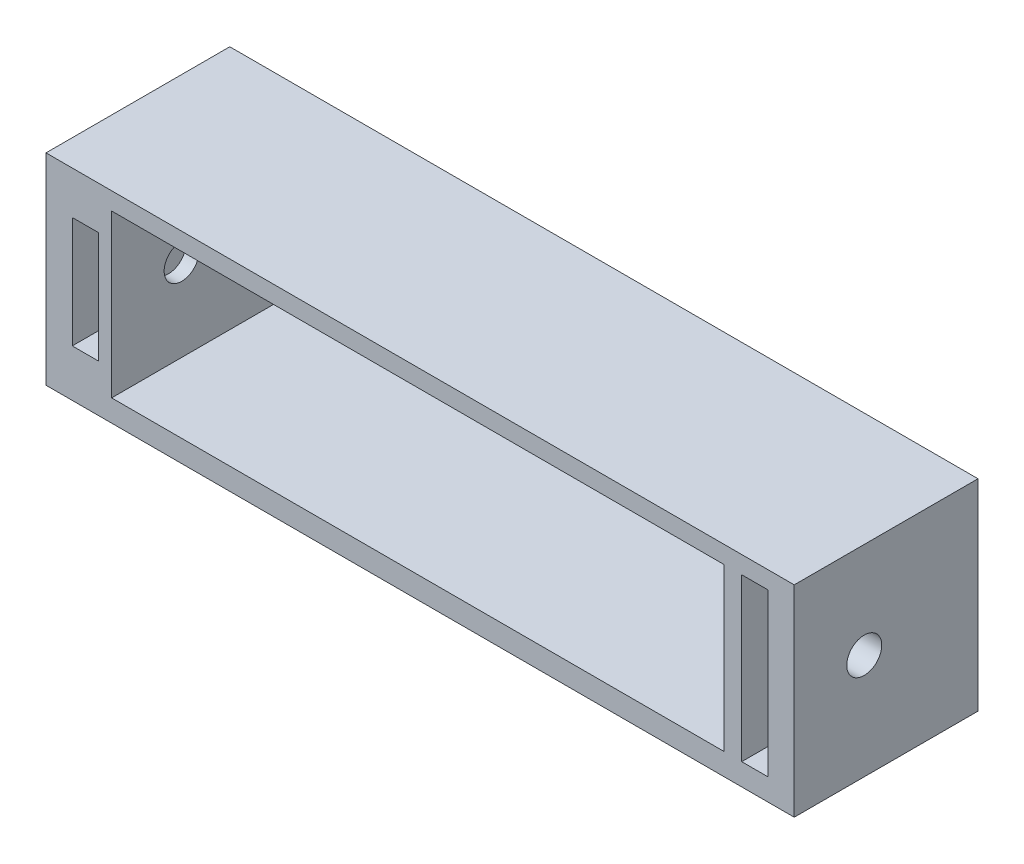
SolidWorks part; units mm, degrees
ref_plane "前基準面" through (0, 0, 0) normal (0, 0, 1) x (1, 0, 0)
ref_plane "上基準面" through (0, 0, 0) normal (0, 1, 0) x (1, 0, 0)
ref_plane "右基準面" through (0, 0, 0) normal (1, 0, 0) x (0, 0, -1)
sketch "草圖1" plane through (0, 0, 0) normal (0, 0, 1) x (1, 0, 0)
  line L0 (25.3269, 9.25) -> (34.5, 9.25)
  line L1 (37.5, -9.25) -> (-37.5, -9.25)
  line L2 (37.5, -9.25) -> (37.5, 9.25)
  line L3 (37.5, 9.25) -> (-37.5, 9.25)
  line L4 (-37.5, -9.25) -> (-37.5, 9.25)
  line L5 (0, 9.25) -> (0, -9.25) construction
  line L6 (37.5, 0) -> (-37.5, 0) construction
  line L7 (34.5, 9.25) -> (34.5, -9.25)
  line L8 (32.5, 9.25) -> (32.5, -9.25)
  line L10 (-36, -6.3557) -> (-39, -6.3557)
  line L12 (-36, 6.3557) -> (-39, 6.3557)
  line L13 (-39, -6.3557) -> (-39, 6.3557)
  line L14 (-37.5, 6.3557) -> (-37.5, -6.3557) construction
  line L15 (-33, 0) -> (-39, 0) construction
  line L16 (-39, 6.3557) -> (-42, 6.3557)
  line L17 (-39, 6.3557) -> (-39, -6.3557)
  line L18 (-39, -6.3557) -> (-42, -6.3557)
  line L19 (-42, 6.3557) -> (-42, -6.3557)
  line L20 (40.5, -11.75) -> (-45, -11.75)
  line L21 (40.5, -11.75) -> (40.5, 11.25)
  line L22 (40.5, 11.25) -> (-45, 11.25)
  line L23 (-45, -11.75) -> (-45, 11.25)
  point P0 (0, 0)
  dimension "D1" = 70
  dimension "D2" = 2
  dimension "D3" = 3
  dimension "D4" = 1.5
  dimension "D5" = 3
  dimension "D6" = 2
  dimension "D7" = 3
  dimension "D8" = 3
  dimension "D9" = 18.5
  dimension "D10" = 23
extrude "填料-伸長1" add sketch "草圖1" along normal blind 19 contours L23 L20 L21 L22 L19 L16 L12 L3 L0 L2 L1 L10 L18 | L13 L10 L4 L12 | L3 L8 L1 L7
sketch "草圖2" plane through (0, 0, 0) normal (0, 0, -1) x (-1, 0, 0)
  line L0 (-40.5, -11.75) -> (-40.5, 11.25) construction
  line L1 (-40.5, 11.25) -> (45, 11.25)
  line L2 (-40.5, 11.25) -> (-40.5, -11.75)
  line L3 (-40.5, -11.75) -> (45, -11.75)
  line L4 (45, 11.25) -> (45, -11.75)
extrude "填料-伸長2" add sketch "草圖2" along normal blind 2
sketch "草圖3" plane through (40.5, 0, 0) normal (1, 0, 0) x (0, 0, -1)
  line L0 (-19, -11.75) -> (-19, 11.25) construction
  circle A0 centre (-11, 0.283) radius 2
  point P4 (-19, -0.25)
  dimension "D1" = 4
  dimension "D2" = 8
extrude "除料-伸長1" cut sketch "草圖3" against normal blind 97 contours A0
